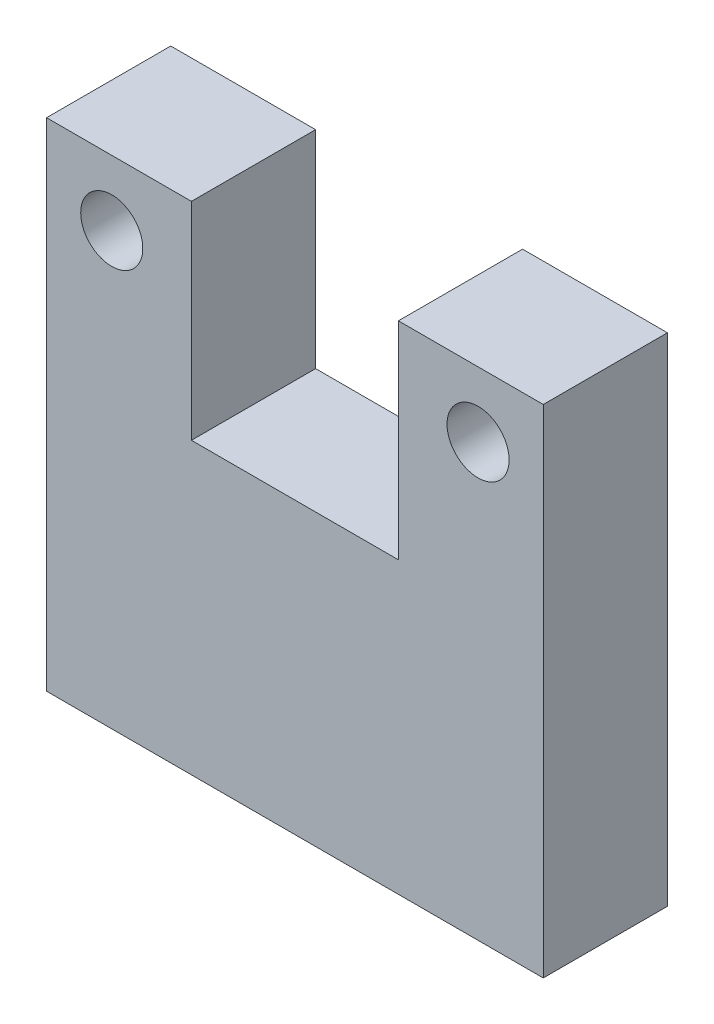
SolidWorks part; units mm, degrees
material "Malleable Cast Iron"
ref_plane "Front Plane" through (0, 0, 0) normal (0, 0, 1) x (1, 0, 0)
ref_plane "Top Plane" through (0, 0, 0) normal (0, 1, 0) x (1, 0, 0)
ref_plane "Right Plane" through (0, 0, 0) normal (1, 0, 0) x (0, 0, -1)
sketch "Sketch1" plane through (0, 0, 0) normal (0, 0, 1) x (1, 0, 0)
  line L0 (0, 0) -> (0, 242.9312) construction
  line L10 (304.8, 304.8) -> (-304.8, 304.8)
  line L11 (304.8, 304.8) -> (304.8, -304.8)
  line L12 (304.8, -304.8) -> (-304.8, -304.8)
  line L13 (-304.8, 304.8) -> (-304.8, -304.8)
  line L14 (304.8, 304.8) -> (-304.8, -304.8) construction
  line L15 (304.8, -304.8) -> (-304.8, 304.8) construction
  line L16 (-127, 50.8) -> (127, 50.8)
  line L18 (-127, 50.8) -> (-127, 304.8)
  line L19 (127, 50.8) -> (127, 304.8)
  line L20 (-127, 304.8) -> (127, 304.8)
  circle A0 centre (-224.8, 224.8) radius 38.1
  circle A1 centre (224.8, 224.8) radius 38.1
  point P5 (0, 0)
  point P11 (0, 0)
  point P12 (0, 50.8)
  dimension "D5" = 76.2
  dimension "D6" = 76.2
  dimension "D1" = 609.6
  dimension "D2" = 609.6
  dimension "D3" = 254
  dimension "D4" = 254
  dimension "D7" = 80
  dimension "D8" = 80
extrude "Boss-Extrude1" add sketch "Sketch1" along normal blind 152.4 contours L19 L16 L18 L10 L13 L12 L11 A1 A0
